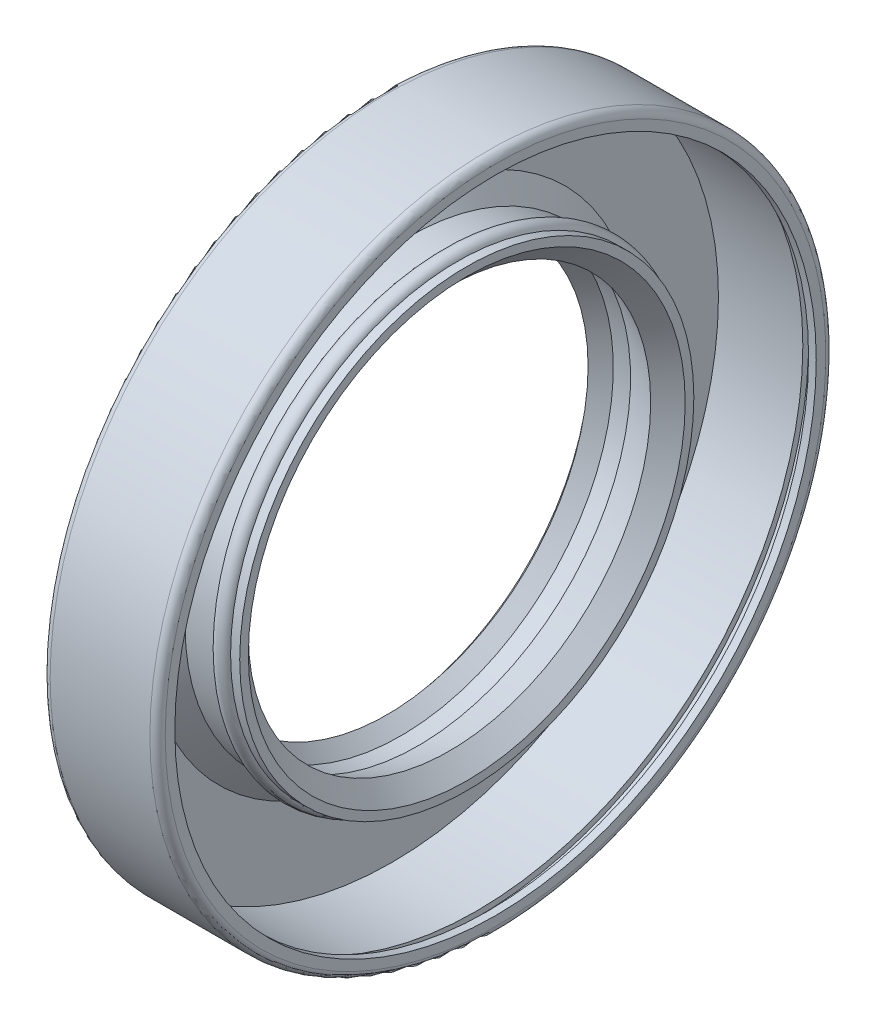
SolidWorks part; units mm, degrees
ref_plane "Plan1" through (0, 0, 0) normal (0, 0, 1) x (1, 0, 0)
ref_plane "Plan2" through (0, 0, 0) normal (0, 1, 0) x (1, 0, 0)
ref_plane "Plan3" through (0, 0, 0) normal (1, 0, 0) x (0, 0, -1)
sketch "Esquisse1" plane through (0, 0, 0) normal (0, 1, 0) x (1, 0, 0)
  line L0 (0, 0) -> (5.9583, 0) construction
  line L1 (0, 13.5725) -> (0, 20.5233)
  line L2 (0.4767, 21) -> (6.6733, 21)
  line L3 (5.9583, 20.285) -> (5.9583, 20.6425)
  line L4 (5.9583, 20.285) -> (0.715, 20.285)
  line L5 (0.715, 20.285) -> (0.715, 15.2082)
  line L6 (2.3256, 13.215) -> (1.2531, 13.215)
  line L7 (1.2531, 13.215) -> (0.4009, 12.5)
  line L8 (0.4009, 12.5) -> (0, 12.9778)
  line L9 (5.9583, 20.6425) -> (6.6733, 20.6425)
  line L10 (0, 12.9778) -> (0.2928, 13.2235)
  line L11 (6.6733, 20.6425) -> (6.6733, 19.9275)
  line L12 (7.15, 19.9275) -> (7.15, 20.5233)
  line L13 (6.6733, 19.9275) -> (7.15, 19.9275)
  line L14 (2.3256, 13.215) -> (4.29, 12.5)
  line L15 (4.29, 12.5) -> (5.3625, 13.5725)
  line L16 (5.3625, 13.5725) -> (5.3625, 14.1088)
  line L17 (5.3625, 14.1088) -> (4.7956, 14.1088)
  line L18 (0.715, 15.2082) -> (1.7875, 13.93)
  line L19 (0.2928, 13.2235) -> (0, 13.5725)
  line L22 (1.7875, 13.93) -> (3.7538, 13.93)
  arc A0 (0, 20.5233) -> (0.4767, 21) centre (0.4767, 20.5233) cw
  arc A1 (4.7956, 14.1088) -> (3.7538, 13.93) centre (4.29, 13.93) ccw
  arc A2 (6.6733, 21) -> (7.15, 20.5233) centre (6.6733, 20.5233) cw
  point P13 (0, 21)
  point P22 (7.15, 21)
  dimension "r" = 0.4767
  dimension "l" = 1.0725
  dimension "D1" = 130
  dimension "De" = 21
  dimension "D3" = 130
  dimension "b" = 7.15
  dimension "e" = 0.715
  dimension "D7" = 45
  dimension "D6" = 20
  dimension "Di" = 12.5
  dimension "pl" = 5.3625
  dimension "h" = 0.1788
revolve "Base-Révolution" add sketch "Esquisse1" angle 360 about L0
sketch "Esquisse2" plane through (0, 0, 0) normal (-1, 0, 0) x (0, 0, 1)
  line L0 (0, 0) -> (13.5725, 0) construction
  line L1 (13.5725, 0) -> (13.93, 0) construction
  circle A1 centre (0, 0) radius 13.5725 construction
  circle A2 centre (0, 0) radius 13.5725 construction
  circle A3 centre (0, 0) radius 13.93
split line "Ligne de séparation1"
equation "\"e@Esquisse1\" = \"b@Esquisse1\"/10"
equation "\"i@Esquisse1\"=\"e@Esquisse1\"/2"
equation "\"r@Esquisse1\"=\"e@Esquisse1\"*2/3"
equation "\"l@Esquisse1\"=\"i@Esquisse1\"*3"
equation "\"pl@Esquisse1\"=\"b@Esquisse1\"*3/4"
equation "\"h@Esquisse1\"=\"i@Esquisse1\"/2"
